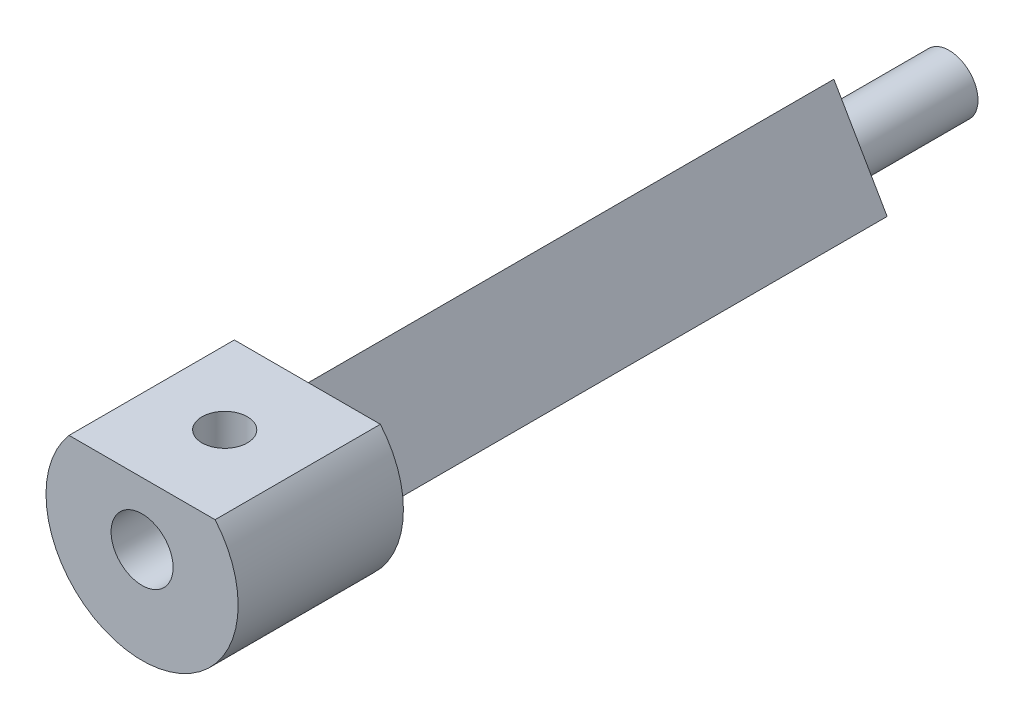
SolidWorks part; units mm, degrees
ref_plane "Front Plane" through (0, 0, 0) normal (0, 0, 1) x (1, 0, 0)
ref_plane "Top Plane" through (0, 0, 0) normal (0, 1, 0) x (1, 0, 0)
ref_plane "Right Plane" through (0, 0, 0) normal (1, 0, 0) x (0, 0, -1)
sketch "Sketch2" plane through (0, 0, 0) normal (0, 0, 1) x (1, 0, 0)
  circle A0 centre (0, 0) radius 6.35
  dimension "D1" = 12.7
extrude "Boss-Extrude1" add sketch "Sketch2" along normal blind 10.922
sketch "Sketch3" plane through (0, 0, 10.922) normal (0, 0, 1) x (1, 0, 0)
  line L1 (-4.8261, 4.1269) -> (6.7389, 4.1269)
  line L2 (-4.8261, 4.1269) -> (-4.8261, 10.0716)
  line L3 (-4.8261, 10.0716) -> (6.7389, 10.0716)
  line L4 (6.7389, 4.1269) -> (6.7389, 10.0716)
  circle A0 centre (0, 0) radius 6.35 construction
extrude "Cut-Extrude1" cut sketch "Sketch3" against normal blind 15.24
sketch "Sketch4" plane through (0, 4.1269, 0) normal (0, 1, 0) x (1, 0, 0)
  line L0 (0, -10.922) -> (0, 0) construction
  line L1 (-4.8261, -10.922) -> (4.8261, -10.922) construction
  circle A0 centre (0, -5.461) radius 1.5
  dimension "D1" = 3
extrude "Cut-Extrude2" cut sketch "Sketch4" against normal blind 5.08
sketch "Sketch6" plane through (0, 0, 10.922) normal (0, 0, 1) x (1, 0, 0)
  circle A0 centre (0, 0) radius 2.05
  dimension "D1" = 4.1
extrude "Cut-Extrude3" cut sketch "Sketch6" against normal blind 10.16
sketch "Sketch8" plane through (0, 0, 0) normal (0, 0, -1) x (-1, 0, 0)
  line L0 (0, 4.064) -> (-3.5195, -2.032)
  line L1 (-3.5195, -2.032) -> (3.5195, -2.032)
  line L2 (3.5195, -2.032) -> (0, 4.064)
  line L3 (0, 0) -> (0, 4.064) construction
  line L4 (0, 0) -> (-3.5195, -2.032) construction
  line L5 (3.5195, -2.032) -> (0, 0) construction
  dimension "D1" = 6.096
extrude "Boss-Extrude2" add sketch "Sketch8" along normal blind 34.798
sketch "Sketch9" plane through (0, 0, -34.798) normal (0, 0, -1) x (-1, 0, 0)
  circle A0 centre (0, 0) radius 1.905
  dimension "D1" = 3.81
extrude "Boss-Extrude3" add sketch "Sketch9" along normal blind 7.62
